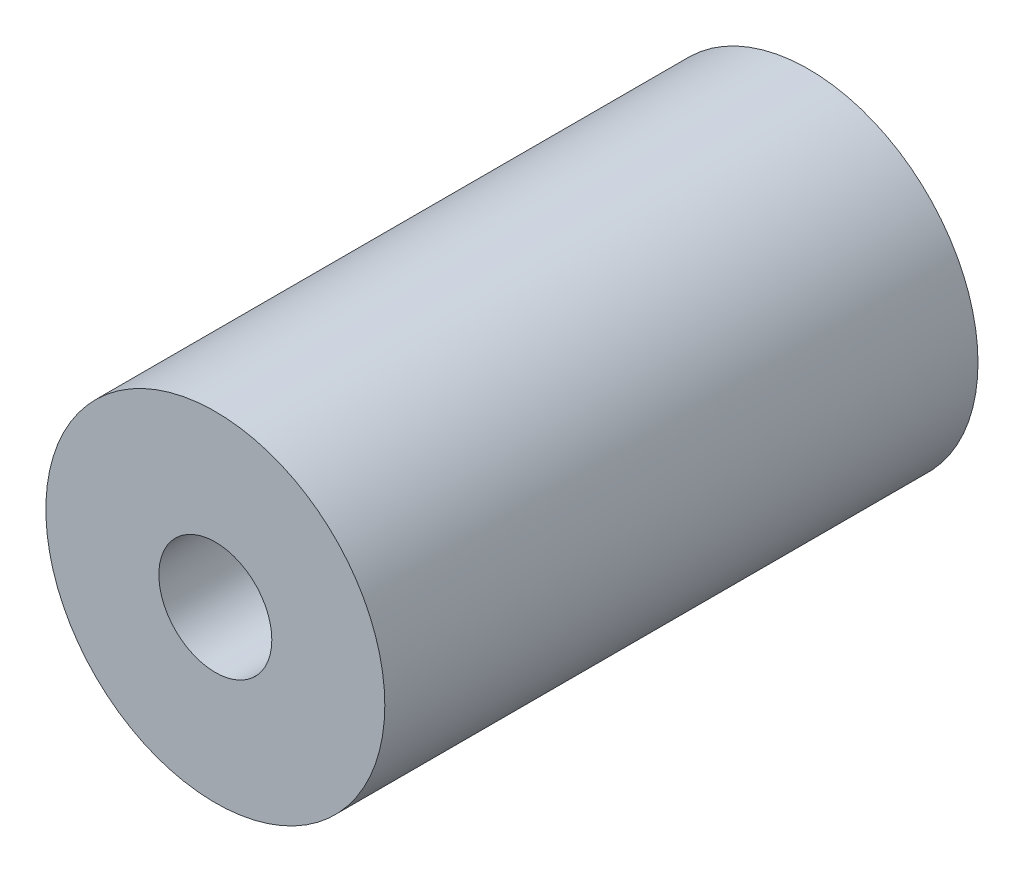
SolidWorks part; units mm, degrees
ref_plane "Front Plane" through (0, 0, 0) normal (0, 0, 1) x (1, 0, 0)
ref_plane "Top Plane" through (0, 0, 0) normal (0, 1, 0) x (1, 0, 0)
ref_plane "Right Plane" through (0, 0, 0) normal (1, 0, 0) x (0, 0, -1)
sketch "Sketch1" plane through (0, 0, 0) normal (0, 0, 1) x (1, 0, 0)
  circle A0 centre (0, 0) radius 30
  circle A1 centre (0, 0) radius 10
  dimension "D1" = 60
  dimension "D2" = 20
extrude "Boss-Extrude1" add sketch "Sketch1" along normal blind 105
